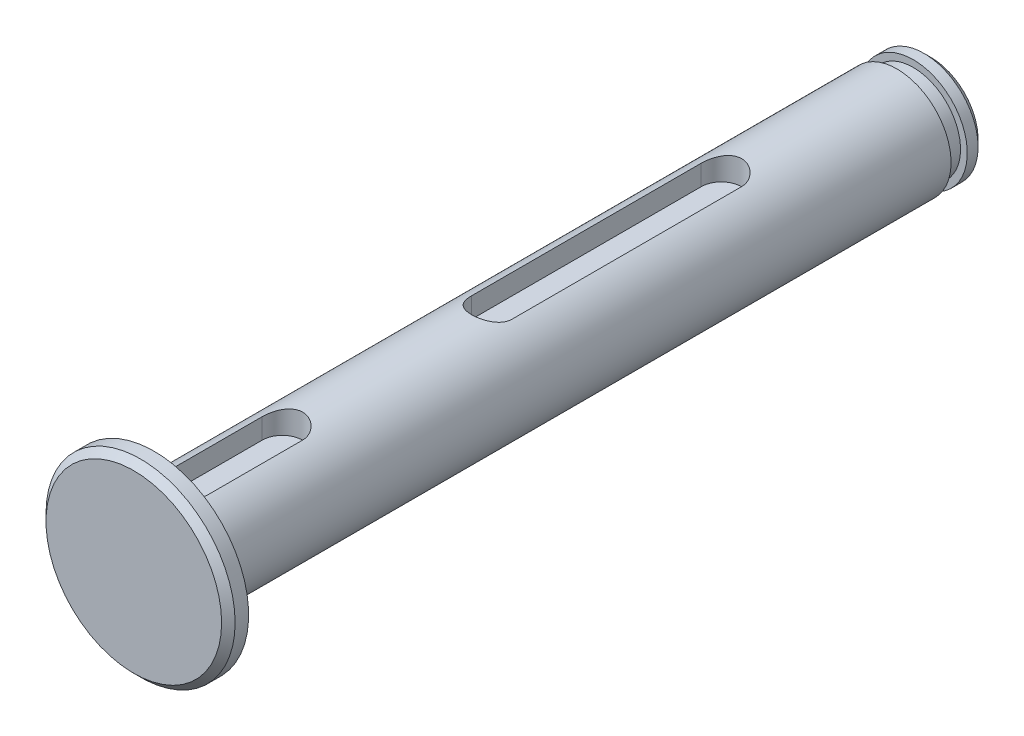
SolidWorks part; units mm, degrees
ref_plane "Front Plane" through (0, 0, 0) normal (0, 0, 1) x (1, 0, 0)
ref_plane "Top Plane" through (0, 0, 0) normal (0, 1, 0) x (1, 0, 0)
ref_plane "Right Plane" through (0, 0, 0) normal (1, 0, 0) x (0, 0, -1)
sketch "Sketch1" plane through (0, 0, 0) normal (0, 1, 0) x (1, 0, 0)
  line L0 (0, 49.3767) -> (0, -72.2586) construction
  line L1 (0, -57.7) -> (-7, -57.7)
  line L2 (-7, -57.7) -> (-7, -56.2)
  line L3 (-7, -56.2) -> (-4, -56.2)
  line L4 (-4, -56.2) -> (-4, -19.9477)
  line L5 (-4, -19.9477) -> (-4, -1.2)
  line L6 (-4, -1.2) -> (-3.5, -1.2)
  line L7 (-3.5, -1.2) -> (-3.5, 0)
  line L8 (-3.5, 0) -> (-4, 0)
  line L9 (-4, 0) -> (-4, 1.3)
  line L10 (-4, 1.3) -> (0, 1.3)
  line L11 (0, -57.7) -> (0, 1.3)
  dimension "D1" = 7
  dimension "D2" = 1.5
  dimension "D3" = 4
  dimension "D4" = 4
  dimension "D5" = 0.5
  dimension "D6" = 4
  dimension "D7" = 1.2
  dimension "D8" = 55
  dimension "D9" = 59
revolve "Revolve1" add sketch "Sketch1" angle 360 about L0
chamfer "Chamfer1" distance 0.5 angle 45 2 edges at (-4, 0, -1.3) (-7, 0, 57.7)
sketch "Sketch2" plane through (0, 0, 0) normal (0, 1, 0) x (1, 0, 0)
  line L0 (0, -12.7) -> (0, -32.7) construction
  line L1 (7, -56.2) -> (-7, -56.2) construction
  line L3 (-1.5, -14.2) -> (-1.5, -31.2)
  line L4 (1.5, -14.2) -> (1.5, -31.2)
  line L5 (-1.5, 1.3) -> (-1.5, -57.7) construction
  line L6 (0, 1.3) -> (0, -57.7) construction
  line L7 (1.5, 1.3) -> (1.5, -57.7) construction
  line L8 (-1.5, -46.7) -> (-1.5, -53.7)
  line L9 (0, -46.7) -> (0, -55.2) construction
  line L10 (1.5, -46.7) -> (1.5, -53.7)
  arc A0 (-1.5, -53.7) -> (1.5, -53.7) centre (0, -53.7) ccw
  arc A1 (1.5, -46.7) -> (-1.5, -46.7) centre (0, -46.7) ccw
  arc A2 (-1.5, -31.2) -> (1.5, -31.2) centre (0, -31.2) ccw
  arc A3 (1.5, -14.2) -> (-1.5, -14.2) centre (0, -14.2) ccw
  dimension "D3" = 17
  dimension "D4" = 1.5
  dimension "D5" = 1.5
  dimension "D7" = 1.5
  dimension "D9" = 1.5
  dimension "D6" = 7
  dimension "D8" = 3
  dimension "D10" = 2.5
  dimension "D11" = 25
  dimension "D1" = 1.5
  dimension "D2" = 1.5
extrude "Cut-Extrude1" cut sketch "Sketch2" along normal blind 10
sketch "Sketch3" plane through (0, 0, 0) normal (0, 1, 0) x (1, 0, 0)
  line L2 (1.5, -31.2) -> (1.5, -14.2)
  line L3 (-1.5, -14.2) -> (-1.5, -31.2)
  line L4 (1.5, -31.2) -> (1.5, -14.2)
  line L5 (-1.5, -14.2) -> (-1.5, -31.2)
  arc A2 (-1.5, -31.2) -> (1.5, -31.2) centre (0, -31.2) ccw
  arc A3 (1.5, -14.2) -> (-1.5, -14.2) centre (0, -14.2) ccw
  arc A4 (-1.5, -31.2) -> (1.5, -31.2) centre (0, -31.2) ccw
  arc A5 (1.5, -14.2) -> (-1.5, -14.2) centre (0, -14.2) ccw
  dimension "D1" = 0
extrude "Extrude1" add sketch "Sketch3" along normal blind 2.2
sketch "Sketch4" plane through (0, 0, 0) normal (0, 1, 0) x (1, 0, 0)
  line L2 (-1.5, -46.7) -> (-1.5, -53.7)
  line L3 (1.5, -53.7) -> (1.5, -46.7)
  line L4 (-1.5, -46.7) -> (-1.5, -53.7)
  line L5 (1.5, -53.7) -> (1.5, -46.7)
  arc A2 (1.5, -46.7) -> (-1.5, -46.7) centre (0, -46.7) ccw
  arc A3 (-1.5, -53.7) -> (1.5, -53.7) centre (0, -53.7) ccw
  arc A4 (1.5, -46.7) -> (-1.5, -46.7) centre (0, -46.7) ccw
  arc A5 (-1.5, -53.7) -> (1.5, -53.7) centre (0, -53.7) ccw
  dimension "D1" = 0
extrude "Extrude2" add sketch "Sketch4" along normal blind 2.2
